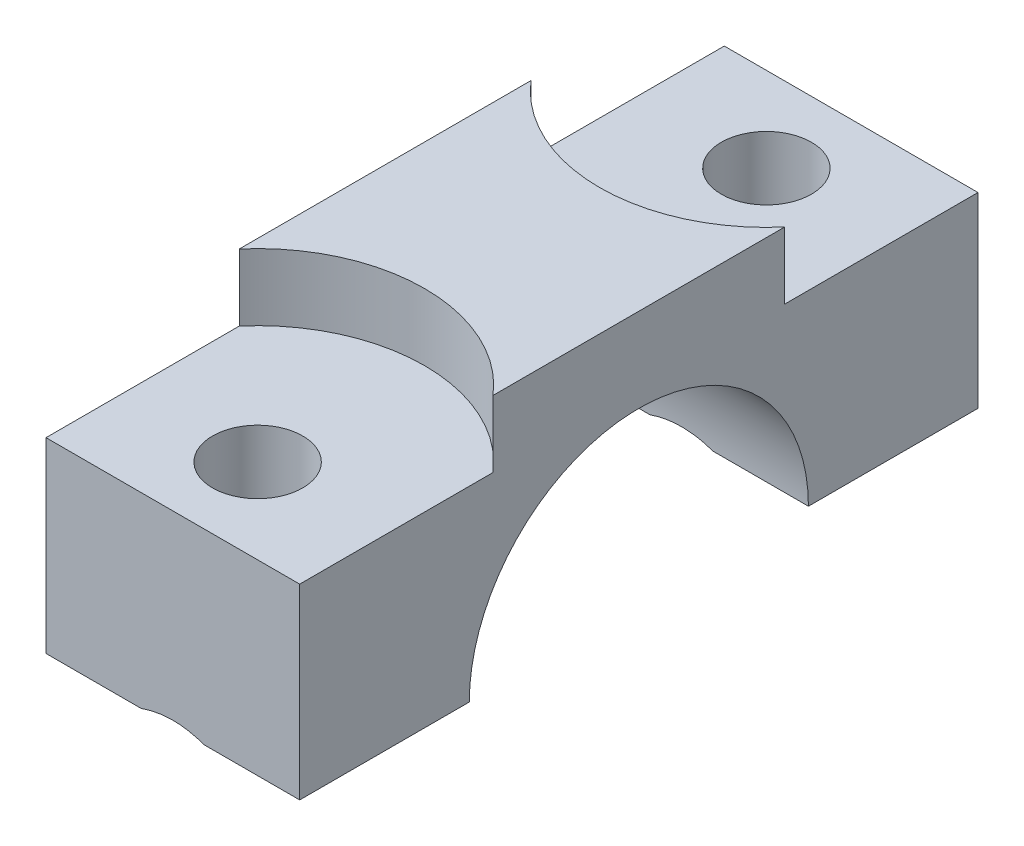
SolidWorks part; units mm, degrees
ref_plane "Front Plane" through (0, 0, 0) normal (0, 0, 1) x (1, 0, 0)
ref_plane "Top Plane" through (0, 0, 0) normal (0, 1, 0) x (1, 0, 0)
ref_plane "Right Plane" through (0, 0, 0) normal (1, 0, 0) x (0, 0, -1)
sketch "Sketch1" plane through (0, 0, 0) normal (1, 0, 0) x (0, 0, -1)
  line L1 (-25.4, 19) -> (25.4, 19)
  line L2 (-25.4, 19) -> (-25.4, 0)
  line L3 (-25.4, 0) -> (25.4, 0)
  line L4 (25.4, 19) -> (25.4, 0)
  circle A0 centre (0, 0) radius 12.7
  dimension "D3" = 25.4
  dimension "D1" = 50.8
  dimension "D2" = 19
extrude "Boss-Extrude1" add sketch "Sketch1" along normal mid plane 19 contours A0 L3 L4 L1 L2
sketch "Sketch2" plane through (0, 0, 0) normal (0, -1, 0) x (1, 0, 0)
  line L0 (0, 25.4) -> (0, 12.7) construction
  line L1 (9.5, 25.4) -> (-9.5, 25.4) construction
  line L2 (9.5, 12.7) -> (-9.5, 12.7) construction
  line L3 (0, -12.7) -> (0, -25.4) construction
  line L4 (9.5, -12.7) -> (-9.5, -12.7) construction
  line L5 (9.5, -25.4) -> (-9.5, -25.4) construction
  point P12 (0, 19.05)
  point P13 (0, -19.05)
  point P14 (0, 0)
hole_wizard "CBORE for M12 Hex Head Cap Screw2" positions "Sketch7" profile "Sketch8" counterbore size "M12" standard "ISO" end condition through all
sketch "Sketch7" plane through (0, 19, 0) normal (0, 1, 0) x (1, 0, 0)
  point P0 (0, 19.05)
  point P3 (0, -19.05)
sketch "Sketch8" plane through (0, 19, -19.05) normal (1, 0, 0) x (0, 0, 1)
  line L0 (0, 0) -> (0, 19)
  line L1 (3.375, 15.6) -> (6.775, 19)
  line L2 (3.375, 15.6) -> (3.375, 5)
  line L3 (3.375, 5) -> (12.5, 5)
  line L4 (12.5, 5) -> (12.5, 0)
  line L5 (12.5, 0) -> (0, 0)
  line L11 (0, -6.35) -> (0, 107.95) construction
  line L12 (6.775, 19) -> (0, 19)
  line L13 (-3.375, 15.6) -> (-6.775, 19) construction
  dimension "Thru Hole Dia." = 6.75
  dimension "Thru Hole Depth" = 19
  dimension "C'Bore Dia." = 25
  dimension "C'Bore Depth" = 5
  dimension "Far C'Sink Dia." = 13.55
  dimension "Far C'Sink Angle" = 90
